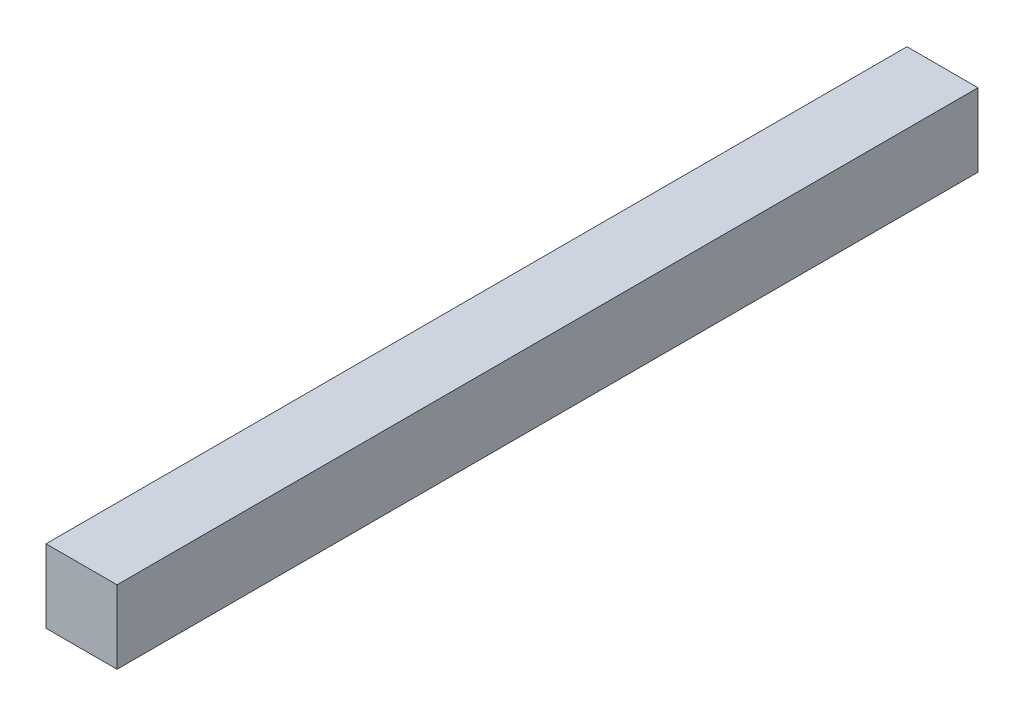
SolidWorks part; units mm, degrees
ref_plane "Front Plane" through (0, 0, 0) normal (0, 0, 1) x (1, 0, 0)
ref_plane "Top Plane" through (0, 0, 0) normal (0, 1, 0) x (1, 0, 0)
ref_plane "Right Plane" through (0, 0, 0) normal (1, 0, 0) x (0, 0, -1)
sketch "Sketch1" plane through (0, 0, 0) normal (0, 0, 1) x (1, 0, 0)
  line L1 (0, 0) -> (25.146, 0)
  line L2 (0, 0) -> (0, 25.908)
  line L3 (0, 25.908) -> (25.146, 25.908)
  line L4 (25.146, 0) -> (25.146, 25.908)
  dimension "D1" = 25.146
  dimension "D2" = 25.908
extrude "Boss-Extrude1" add sketch "Sketch1" along normal blind 304.8
equation "\"baseplate_thickness\"=0.47"
equation "\"baseplate_length\"= 12"
equation "\"baseplate_width\"= 4"
equation "\"slider_width\"= 2"
equation "\"slider_length\"= 4"
equation "\"slider_thickness\"= 1"
equation "\"side_radial_clearance\"= 0.01"
equation "\"front_radial_clearance\"= 0.01"
equation "\"side_plate_width\"= (\"baseplate_width\" - \"slider_width\" - ( 2 * \"side_radial_clearance\" ))/2"
equation "\"side_plate_height\"= \"slider_thickness\" + ( 2 * \"front_radial_clearance\" )"
equation "\"keeper_plate_thickness\"= 0.5"
equation "\"rail_width\"= 1"
equation "\"rail_radial_clearance\"= 0.25"
equation "\"D1@Sketch1\"=\"side_plate_width\""
equation "\"D2@Sketch1\"=\"side_plate_height\""
equation "\"D1@Boss-Extrude1\"=\"baseplate_length\""
